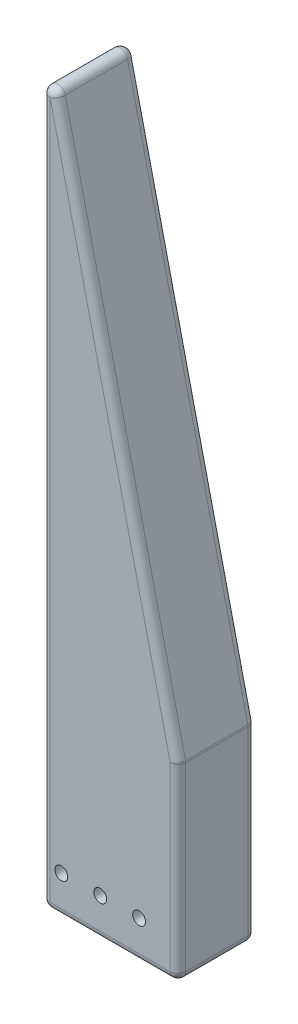
SolidWorks part; units mm, degrees
ref_plane "Front" through (0, 0, 0) normal (0, 0, 1) x (1, 0, 0)
ref_plane "Top" through (0, 0, 0) normal (0, 1, 0) x (1, 0, 0)
ref_plane "Right" through (0, 0, 0) normal (1, 0, 0) x (0, 0, -1)
sketch "Sketch2" plane through (0, 0, 0) normal (0, 0, 1) x (1, 0, 0)
  line L0 (92.9226, -246.0833) -> (92.9226, 46.0167) construction
  line L1 (92.9226, 8.0437) -> (48.5996, 8.0437)
  line L2 (92.9226, 8.0437) -> (92.9226, 69.9575)
  line L3 (92.9226, 69.9575) -> (48.5996, 260.3004)
  line L4 (48.5996, 8.0437) -> (48.5996, 260.3004)
  line L5 (48.5996, 10.2027) -> (48.5996, 31.2847) construction
  line L6 (116.0366, 8.0437) -> (50.7586, 8.0437) construction
  line L7 (96.1338, 56.1673) -> (70.6674, 165.5314) construction
  point P0 (0, 0)
extrude "Boss-Extrude2" add sketch "Sketch2" along normal blind 25.4
hole_wizard "#8 Clearance Hole1" positions "Sketch4" profile "Sketch5" hole size "#8" standard "ANSI Inch" end condition through all
sketch "Sketch4" plane through (0, 0, 0) normal (0, 0, -1) x (-1, 0, 0)
  point P0 (-80.2226, 20.6167)
  point P3 (-67.5226, 20.6167)
  point P6 (-54.8226, 20.6167)
sketch "Sketch5" plane through (80.2226, 20.6167, 0) normal (1, 0, 0) x (0, 1, 0)
  line L0 (0, 0) -> (0, 25.4)
  line L1 (0, 25.4) -> (2.0955, 25.4)
  line L2 (2.0955, 25.4) -> (2.0955, 0)
  line L5 (2.0955, 0) -> (0, 0)
  line L11 (0, -6.35) -> (0, 107.95) construction
  dimension "Thru Hole Dia." = 4.191
  dimension "Thru Hole Depth" = 25.4
fillet "Fillet1" radius 2.54 12 edges at (48.5996, 8.0437, 12.7) (70.7611, 165.1289, 25.4) (48.5996, 134.172, 25.4) (48.5996, 134.172, 0) (70.7611, 8.0437, 25.4) (70.7611, 8.0437, 0) (70.7611, 165.1289, 0) (92.9226, 39.0006, 0) (92.9226, 39.0006, 25.4) (92.9226, 8.0437, 12.7) (92.9226, 69.9575, 12.7) (48.5996, 260.3004, 12.7)
